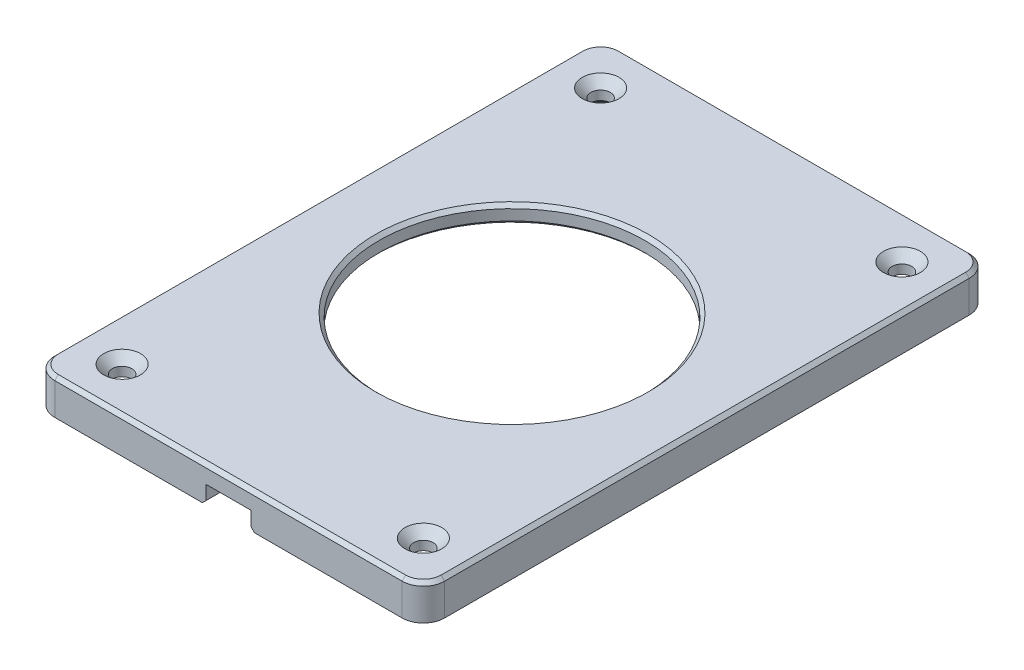
SolidWorks part; units mm, degrees
material "99.5% Aluminum Oxide"
ref_plane "Front Plane" through (0, 0, 0) normal (0, 0, 1) x (1, 0, 0)
ref_plane "Top Plane" through (0, 0, 0) normal (0, 1, 0) x (1, 0, 0)
ref_plane "Right Plane" through (0, 0, 0) normal (1, 0, 0) x (0, 0, -1)
sketch "Sketch1" plane through (0, 0, 0) normal (0, 1, 0) x (1, 0, 0)
  line L1 (-50, -75) -> (50, -75)
  line L2 (-50, -75) -> (-50, 75)
  line L3 (-50, 75) -> (50, 75)
  line L4 (50, -75) -> (50, 75)
  line L5 (-50, -75) -> (50, 75) construction
  line L6 (-50, 75) -> (50, -75) construction
  point P0 (0, 0)
  dimension "D1" = 150
  dimension "D2" = 100
extrude "Boss-Extrude1" add sketch "Sketch1" along normal mid plane 5
sketch "Sketch2" plane through (0, 2.5, 0) normal (0, 1, 0) x (1, 0, 0)
  line L0 (-50, 75) -> (-50, -75) construction
  line L1 (-42.5, -67.5) -> (42.5, -67.5) construction
  line L2 (-42.5, -67.5) -> (-42.5, 67.5) construction
  line L3 (-42.5, 67.5) -> (42.5, 67.5) construction
  line L4 (42.5, -67.5) -> (42.5, 67.5) construction
  line L5 (-42.5, -67.5) -> (42.5, 67.5) construction
  line L6 (-42.5, 67.5) -> (42.5, -67.5) construction
  line L7 (50, 75) -> (-50, 75) construction
  circle A0 centre (-42.5, 67.5) radius 2.5 construction
  point P0 (0, 0)
  point P7 (-45, 67.5)
  point P8 (-42.5, 70)
  dimension "D3" = 5
  dimension "D1" = 5
  dimension "D2" = 5
hole_wizard "CSK for M5 Flat Head Machine Screw1" positions "3DSketch1" profile "Sketch4" countersink size "M5" standard "ANSI Metric" end condition through all
sketch3d "3DSketch1"
  point P0 (-42.5, 2.5, -67.5)
  point P3 (42.5, 2.5, -67.5)
  point P6 (42.5, 2.5, 67.5)
  point P9 (-42.5, 2.5, 67.5)
sketch "Sketch4" plane through (-42.5, 2.5, -67.5) normal (1, 0, 0) x (0, 0, 1)
  line L0 (0, 0) -> (0, 5)
  line L1 (0, 5) -> (2.75, 5)
  line L2 (2.75, 5) -> (2.75, 2.45)
  line L3 (2.75, 2.45) -> (5.2, 0)
  line L5 (5.2, 0) -> (0, 0)
  line L6 (-2.75, 2.45) -> (-5.2, 0) construction
  line L11 (0, -6.35) -> (0, 107.95) construction
  dimension "Thru Hole Dia." = 5.5
  dimension "Thru Hole Depth" = 5
  dimension "Near C'Sink Dia." = 10.4
  dimension "Near C'Sink Angle" = 90
sketch "Sketch5" plane through (0, 2.5, 0) normal (0, 1, 0) x (1, 0, 0)
  line L0 (-50, -75) -> (50, -75) construction
  line L1 (50, -75) -> (50, 75) construction
  line L2 (50, 75) -> (-50, 75) construction
  line L3 (-50, 75) -> (-50, -75) construction
  line L4 (-50, -75) -> (50, -75)
  line L5 (50, -75) -> (50, 75)
  line L6 (50, 75) -> (-50, 75)
  line L7 (-50, 75) -> (-50, -75)
  line L9 (-55, -80) -> (55, -80)
  line L10 (-55, -80) -> (-55, 80)
  line L11 (-55, 80) -> (55, 80)
  line L12 (55, -80) -> (55, 80)
  line L13 (-55, -80) -> (55, 80) construction
  line L14 (-55, 80) -> (55, -80) construction
  point P2 (0, 0)
  dimension "D1" = 5
  dimension "D2" = 5
extrude "Boss-Extrude2" add sketch "Sketch5" against normal blind 10
sketch "Sketch6" plane through (0, -7.5, 0) normal (0, -1, 0) x (1, 0, 0)
  line L0 (0, 0) -> (0, 50000) construction
  line L1 (-55, 80) -> (55, 80) construction
  line L2 (-6.35, 75) -> (6.35, 75)
  line L3 (-6.35, 75) -> (-6.35, 80)
  line L4 (-6.35, 80) -> (6.35, 80)
  line L5 (6.35, 75) -> (6.35, 80)
  line L6 (-6.35, 75) -> (6.35, 80) construction
  line L7 (-6.35, 80) -> (6.35, 75) construction
  line L8 (-50, 75) -> (50, 75) construction
  point P3 (0, 77.5)
  dimension "D1" = 12.7
extrude "Cut-Extrude1" cut sketch "Sketch6" against normal up to surface (5 mm away) up to face at (-42.5, -2.5, -64.75)
fillet "Fillet1" radius 6 8 edges at (55, -2.5, 80) (55, -2.5, -80) (-55, -2.5, -80) (-55, -2.5, 80) (-50, -5, -75) (50, -5, -75) (50, -5, 75) (-50, -5, 75)
sketch "Sketch7" plane through (0, 2.5, 0) normal (0, 1, 0) x (1, 0, 0)
  circle A0 centre (0, 0) radius 37.5
  dimension "D1" = 75
extrude "Cut-Extrude2" cut sketch "Sketch7" against normal through all both and the other way through all
chamfer "Chamfer2" distance 1 angle 45 21 edges at (6.35, -7.5, 77.5) (-6.35, -7.5, 77.5) (25.175, -7.5, 75) (48.2426, -7.5, 73.2426) (50, -7.5, 0) (48.2426, -7.5, -73.2426) (0, -7.5, -75) (-25.175, -7.5, 75) (-48.2426, -7.5, -73.2426) (-48.2426, -7.5, 73.2426) (-50, -7.5, 0) (0, 2.5, -37.5) (-55, 2.5, 0) (-53.2426, 2.5, 78.2426) (-53.2426, 2.5, -78.2426) (0, 2.5, 80) (0, 2.5, -80) (53.2426, 2.5, 78.2426) (53.2426, 2.5, -78.2426) (55, 2.5, 0) (0, -2.5, -37.5)
